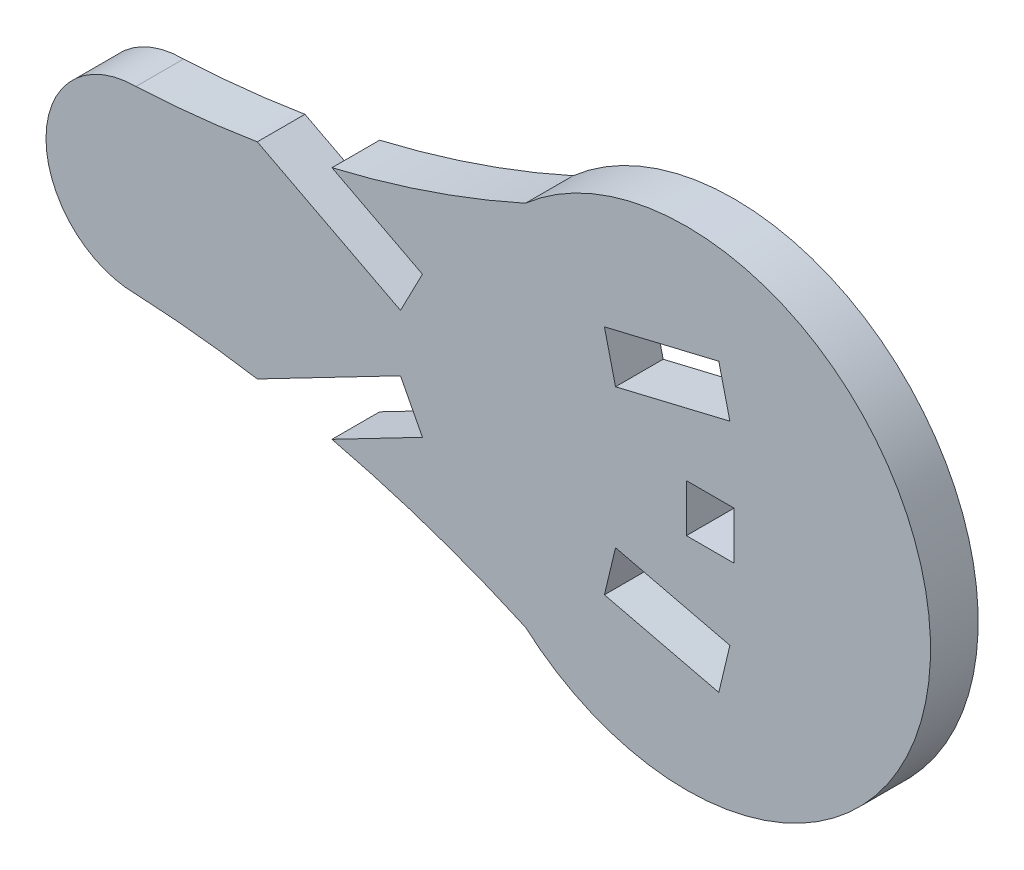
SolidWorks part; units mm, degrees
ref_plane "Front Plane" through (0, 0, 0) normal (0, 0, 1) x (1, 0, 0)
ref_plane "Top Plane" through (0, 0, 0) normal (0, 1, 0) x (1, 0, 0)
ref_plane "Right Plane" through (0, 0, 0) normal (1, 0, 0) x (0, 0, -1)
sketch "Sketch1" plane through (0, 0, 0) normal (0, 0, 1) x (1, 0, 0)
  line L0 (0, 0) -> (0, -1.524) construction
  line L2 (-17.6, -1.524) -> (-17.6, 0) construction
  line L3 (5.9006, -0.762) -> (11.8064, -0.762) construction
  line L4 (5.9006, -1.524) -> (5.9006, 0) construction
  line L6 (1.524, 0) -> (0, 0)
  line L7 (1.524, 0) -> (1.524, -1.524)
  line L8 (1.524, -1.524) -> (0, -1.524)
  line L9 (0, 0) -> (0, -1.524)
  arc A0 (-5.145, -6.6322) -> (-5.145, 5.1082) centre (0, -0.762) ccw
  arc A1 (-17.6, -3.637) -> (-5.145, -6.6322) centre (-19.2381, -37.8424) cw
  arc A2 (-17.6, 2.113) -> (-17.6, -3.637) centre (-17.6, -0.762) ccw
  arc A3 (-17.6, 2.113) -> (-5.145, 5.1082) centre (-19.2381, 36.3184) ccw
extrude "Boss-Extrude1" add sketch "Sketch1" against normal blind 1.524
sketch "Sketch2" plane through (0, 0, 0) normal (0, 0, 1) x (1, 0, 0)
  line L0 (-8.79, -2.3437) -> (-13.5815, -4.8323) construction
  line L1 (-9.1412, -1.6675) -> (-13.9327, -4.1561)
  line L2 (-8.4388, -3.0199) -> (-13.2303, -5.5085)
  line L3 (-9.1412, -1.6675) -> (-8.4388, -3.0199)
  line L4 (-13.9327, -4.1561) -> (-13.2303, -5.5085)
  line L5 (0, -0.762) -> (-5.0943, -0.762) construction
  line L6 (0, 0) -> (0, -1.524) construction
  line L7 (-13.9327, 2.6321) -> (-13.2303, 3.9845)
  line L8 (-9.1412, 0.1435) -> (-8.4388, 1.4959)
  line L9 (-8.4388, 1.4959) -> (-13.2303, 3.9845)
  line L10 (-9.1412, 0.1435) -> (-13.9327, 2.6321)
extrude "Cut-Extrude1" cut sketch "Sketch2" against normal blind 2.54
sketch "Sketch3" plane through (0, 0, 0) normal (0, 0, 1) x (1, 0, 0)
  line L0 (1.0359, 3.8233) -> (1.3906, 2.3412)
  line L1 (-2.6208, -4.4722) -> (1.0359, -5.3473)
  line L2 (-2.2661, -2.9901) -> (1.3906, -3.8652)
  line L3 (-2.6208, -4.4722) -> (-2.2661, -2.9901)
  line L4 (1.0359, -5.3473) -> (1.3906, -3.8652)
  line L5 (0, -0.762) -> (1.524, -0.762) construction
  line L6 (0, 0) -> (0, -1.524) construction
  line L7 (1.524, -1.524) -> (1.524, 0) construction
  line L8 (-2.6208, 2.9482) -> (-2.2661, 1.4661)
  line L9 (-2.2661, 1.4661) -> (1.3906, 2.3412)
  line L10 (-2.6208, 2.9482) -> (1.0359, 3.8233)
extrude "Cut-Extrude2" cut sketch "Sketch3" against normal blind 2.54
